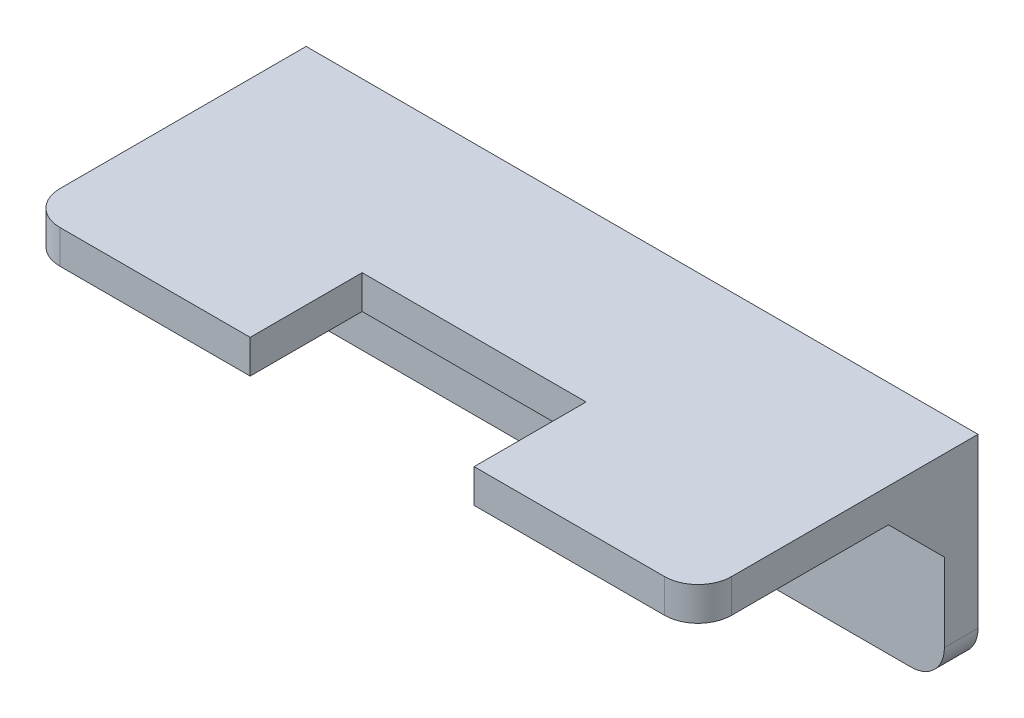
SolidWorks part; units mm, degrees
ref_plane "Front Plane" through (0, 0, 0) normal (0, 0, 1) x (1, 0, 0)
ref_plane "Top Plane" through (0, 0, 0) normal (0, 1, 0) x (1, 0, 0)
ref_plane "Right Plane" through (0, 0, 0) normal (1, 0, 0) x (0, 0, -1)
sketch "Sketch1" plane through (0, 0, 0) normal (0, 0, 1) x (1, 0, 0)
  line L0 (80, 160) -> (-80, 160) construction
  line L1 (-30, 160) -> (30, 160)
  line L2 (-30, 160) -> (-30, 157)
  line L3 (-30, 157) -> (30, 157)
  line L4 (30, 160) -> (30, 157)
  line L5 (0, 164) -> (0, 138.3232) construction
  line L6 (-4.5, 164) -> (4.5, 164) construction
  dimension "D1" = 30
  dimension "D2" = 60
  dimension "D3" = 3
extrude "Boss-Extrude1" add sketch "Sketch1" along normal blind 25
sketch "Sketch2" plane through (0, 157, 0) normal (0, -1, 0) x (1, 0, 0)
  line L0 (30, 25) -> (30, 0) construction
  line L1 (-30, 0) -> (30, 0)
  line L2 (-30, 0) -> (-30, 3)
  line L3 (-30, 3) -> (30, 3)
  line L4 (30, 0) -> (30, 3)
  dimension "D1" = 3
extrude "Boss-Extrude2" add sketch "Sketch2" along normal blind 15
sketch "Sketch3" plane through (0, 157, 0) normal (0, -1, 0) x (1, 0, 0)
  line L0 (-30, 25) -> (30, 25) construction
  line L1 (-10, 25) -> (10, 25)
  line L2 (-10, 25) -> (-10, 15)
  line L3 (-10, 15) -> (10, 15)
  line L4 (10, 25) -> (10, 15)
  line L5 (30, 25) -> (30, 3) construction
  line L6 (-30, 25) -> (-30, 3) construction
  dimension "D1" = 20
  dimension "D2" = 20
  dimension "D3" = 10
extrude "Cut-Extrude1" cut sketch "Sketch3" against normal through all
fillet "Fillet1" radius 3 4 edges at (-30, 142, 1.5) (30, 142, 1.5) (30, 158.5, 25) (-30, 158.5, 25)
chamfer "Chamfer1" distance 5 angle 45 1 edges at (0, 157, 3)
